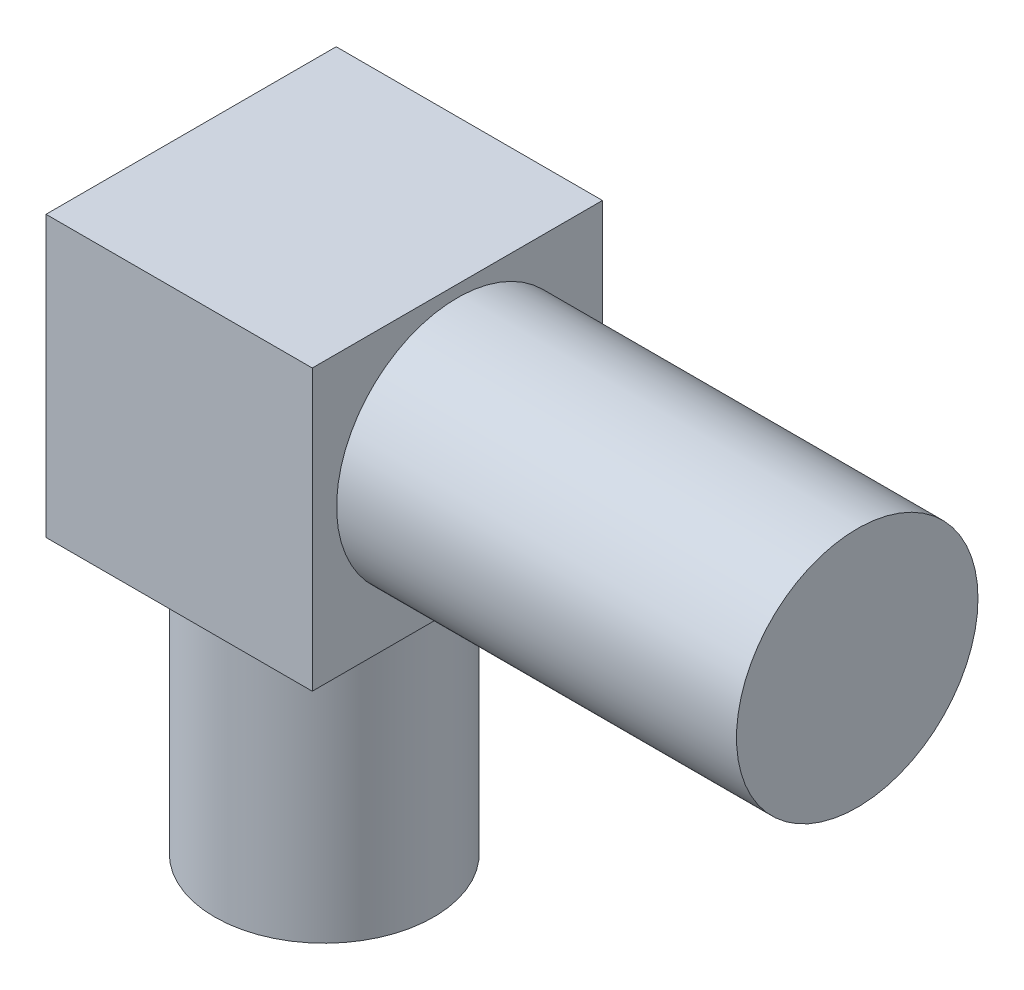
SolidWorks part; units mm, degrees
ref_plane "Front Plane" through (0, 0, 0) normal (0, 0, 1) x (1, 0, 0)
ref_plane "Top Plane" through (0, 0, 0) normal (0, 1, 0) x (1, 0, 0)
ref_plane "Right Plane" through (0, 0, 0) normal (1, 0, 0) x (0, 0, -1)
sketch "Sketch1" plane through (0, 0, 0) normal (0, 1, 0) x (1, 0, 0)
  circle A0 centre (0, 0) radius 21.9211
extrude "Boss-Extrude1" add sketch "Sketch1" along normal blind 56
sketch "Sketch2" plane through (0, 56, 0) normal (0, 1, 0) x (1, 0, 0)
  line L1 (-26.6335, -29.0268) -> (26.6335, -29.0268)
  line L2 (-26.6335, -29.0268) -> (-26.6335, 29.0268)
  line L3 (-26.6335, 29.0268) -> (26.6335, 29.0268)
  line L4 (26.6335, -29.0268) -> (26.6335, 29.0268)
  line L5 (-26.6335, -29.0268) -> (26.6335, 29.0268) construction
  line L6 (-26.6335, 29.0268) -> (26.6335, -29.0268) construction
  point P0 (0, 0)
extrude "Boss-Extrude2" add sketch "Sketch2" along normal blind 56
sketch "Sketch3" plane through (26.6335, 0, 0) normal (1, 0, 0) x (0, 0, -1)
  circle A0 centre (0, 85.4953) radius 24.1568
extrude "Boss-Extrude3" add sketch "Sketch3" along normal blind 80
